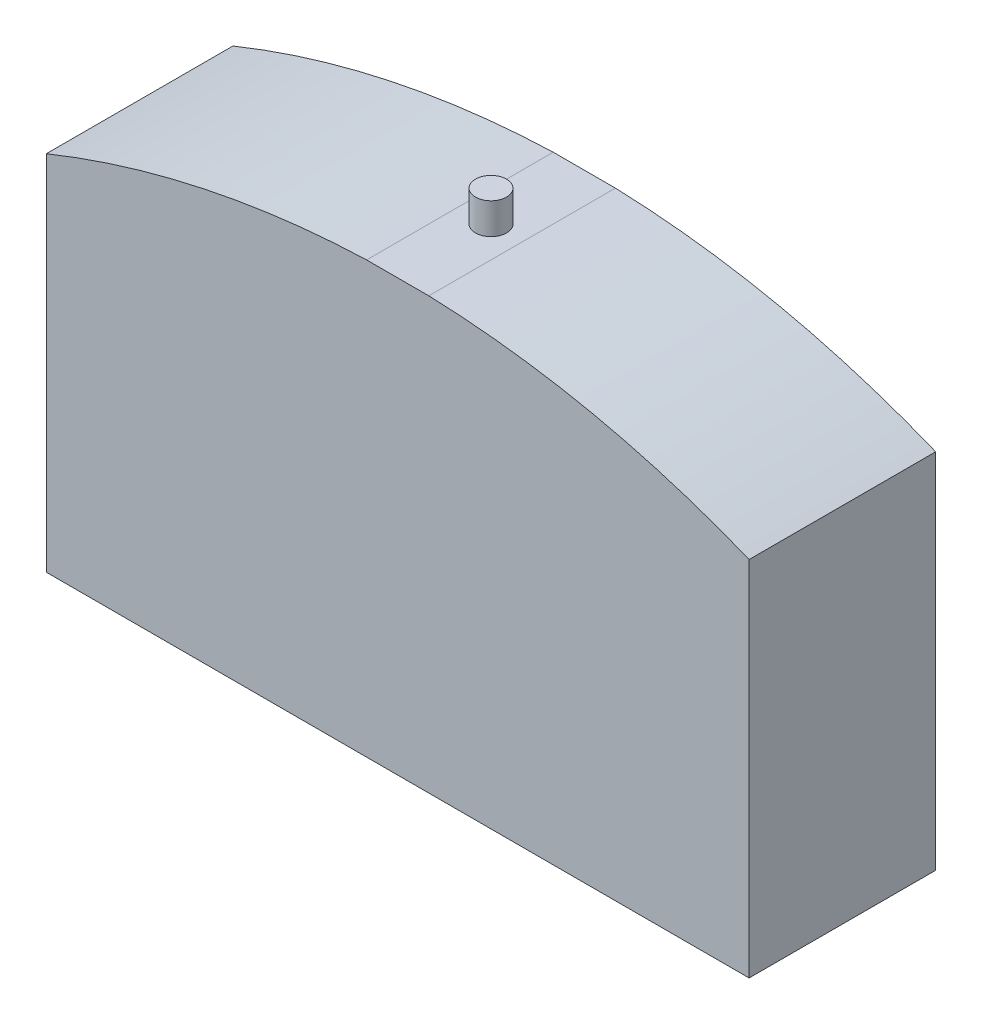
SolidWorks part; units mm, degrees
ref_plane "Front Plane" through (0, 0, 0) normal (0, 0, 1) x (1, 0, 0)
ref_plane "Top Plane" through (0, 0, 0) normal (0, 1, 0) x (1, 0, 0)
ref_plane "Right Plane" through (0, 0, 0) normal (1, 0, 0) x (0, 0, -1)
sketch "Sketch1" plane through (0, 0, 0) normal (0, 0, 1) x (1, 0, 0)
  line L0 (0, 0) -> (0, 149.9166) construction
  line L1 (-5, 149.9166) -> (5, 149.9166)
  line L3 (-56.5, 138.9523) -> (-56.5, 80.6823)
  line L4 (-56.5, 80.6823) -> (56.5, 80.6823)
  line L5 (56.5, 138.9523) -> (56.5, 80.6823)
  arc A0 (56.5, 138.9523) -> (5, 149.9166) centre (0, 0) ccw
  arc A1 (-5, 149.9166) -> (-56.5, 138.9523) centre (0, 0) ccw
  dimension "D1" = 300
  dimension "D2" = 113
  dimension "D3" = 58.27
  dimension "D4" = 10
extrude "Boss-Extrude1" add sketch "Sketch1" along normal blind 30
sketch "Sketch2" plane through (0, 0, 0) normal (0, 0, -1) x (-1, 0, 0)
  line L8 (4.9497, 146.9166) -> (-4.9497, 146.9166)
  line L9 (-53.5, 136.9188) -> (-53.5, 83.6823)
  line L10 (-53.5, 83.6823) -> (53.5, 83.6823)
  line L11 (53.5, 83.6823) -> (53.5, 136.9188)
  line L12 (4.9497, 146.9166) -> (-4.9497, 146.9166)
  line L13 (-53.5, 136.9188) -> (-53.5, 83.6823)
  line L14 (-53.5, 83.6823) -> (53.5, 83.6823)
  line L15 (53.5, 83.6823) -> (53.5, 136.9188)
  arc A4 (53.5, 136.9188) -> (4.9497, 146.9166) centre (0, 0) ccw
  arc A5 (-4.9497, 146.9166) -> (-53.5, 136.9188) centre (0, 0) ccw
  arc A6 (53.5, 136.9188) -> (4.9497, 146.9166) centre (0, 0) ccw
  arc A7 (-4.9497, 146.9166) -> (-53.5, 136.9188) centre (0, 0) ccw
  dimension "D1" = 3
extrude "Cut-Extrude1" cut sketch "Sketch2" against normal blind 27
sketch "Sketch3" plane through (0, 149.9166, 0) normal (0, 1, 0) x (1, 0, 0)
  line L0 (0, 0) -> (0, -30) construction
  line L1 (5, -30) -> (-5, -30) construction
  line L2 (-5, -15) -> (5, -15) construction
  line L3 (-5, -30) -> (-5, 0) construction
  line L4 (5, -30) -> (5, 0) construction
  circle A0 centre (0, -15) radius 2.5
  dimension "D1" = 5
extrude "Boss-Extrude2" add sketch "Sketch3" along normal blind 5
